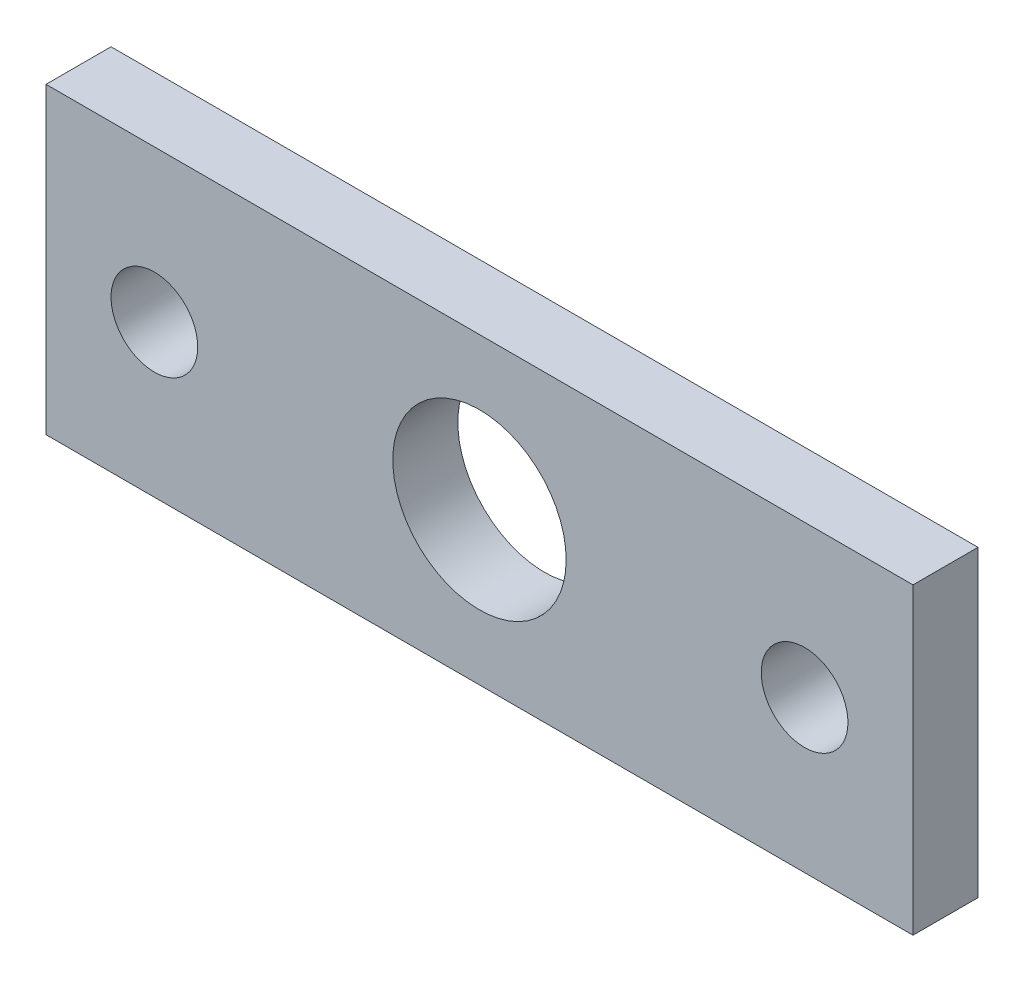
SolidWorks part; units mm, degrees
ref_plane "Front Plane" through (0, 0, 0) normal (0, 0, 1) x (1, 0, 0)
ref_plane "Top Plane" through (0, 0, 0) normal (0, 1, 0) x (1, 0, 0)
ref_plane "Right Plane" through (0, 0, 0) normal (1, 0, 0) x (0, 0, -1)
sketch "Sketch1" plane through (0, 0, 0) normal (0, 0, 1) x (1, 0, 0)
  line L1 (-40, -18) -> (-80, -18)
  line L2 (-40, -18) -> (-40, -32)
  line L3 (-40, -32) -> (-80, -32)
  line L4 (-80, -18) -> (-80, -32)
  line L5 (-40, -18) -> (-80, -32) construction
  line L6 (-40, -32) -> (-80, -18) construction
  circle A0 centre (-45, -25) radius 2
  circle A1 centre (-75, -25) radius 2
  circle A2 centre (-60, -25) radius 4
  point P13 (-60, -25)
  dimension "D1" = 8
  dimension "D2" = 4
  dimension "D3" = 4
  dimension "D4" = 7
  dimension "D5" = 7
  dimension "D6" = 5
  dimension "D7" = 5
extrude "Boss-Extrude1" add sketch "Sketch1" along normal blind 3
